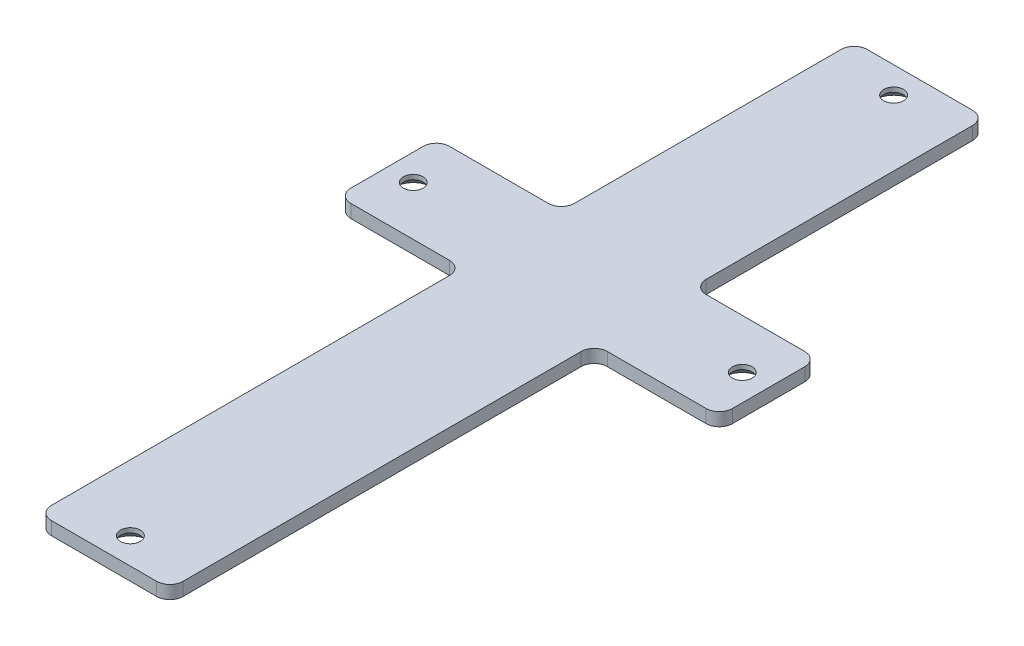
SolidWorks part; units mm, degrees
ref_plane "Front Plane" through (0, 0, 0) normal (0, 0, 1) x (1, 0, 0)
ref_plane "Top Plane" through (0, 0, 0) normal (0, 1, 0) x (1, 0, 0)
ref_plane "Right Plane" through (0, 0, 0) normal (1, 0, 0) x (0, 0, -1)
sketch "Sketch1" plane through (0, 0, 0) normal (0, 1, 0) x (1, 0, 0)
  line L0 (12, 17.5) -> (27, 17.5)
  line L1 (-8, -62) -> (8, -62)
  line L2 (-10, -60) -> (-10, 0.5)
  line L3 (-8, 62) -> (8, 62)
  line L4 (10, -60) -> (10, 0.5)
  line L5 (-10, -62) -> (10, 62) construction
  line L6 (-10, 62) -> (10, -62) construction
  line L7 (-27, 2.5) -> (-12, 2.5)
  line L8 (-29, 4.5) -> (-29, 15.5)
  line L9 (-27, 17.5) -> (-12, 17.5)
  line L10 (29, 4.5) -> (29, 15.5)
  line L11 (-29, 2.5) -> (29, 17.5) construction
  line L12 (-29, 17.5) -> (29, 2.5) construction
  line L13 (10, 19.5) -> (10, 60)
  line L14 (-10, 19.5) -> (-10, 60)
  line L16 (12, 2.5) -> (27, 2.5)
  circle A0 centre (0, 58) radius 1.5
  circle A1 centre (0, -58) radius 1.5
  circle A2 centre (25, 10) radius 1.5
  circle A3 centre (-25, 10) radius 1.5
  arc A4 (-10, 60) -> (-8, 62) centre (-8, 60) cw
  arc A5 (10, 0.5) -> (12, 2.5) centre (12, 0.5) cw
  arc A6 (-12, 17.5) -> (-10, 19.5) centre (-12, 19.5) ccw
  arc A7 (-27, 2.5) -> (-29, 4.5) centre (-27, 4.5) cw
  arc A8 (27, 17.5) -> (29, 15.5) centre (27, 15.5) cw
  arc A9 (-8, -62) -> (-10, -60) centre (-8, -60) cw
  arc A10 (8, 62) -> (10, 60) centre (8, 60) cw
  arc A11 (8, -62) -> (10, -60) centre (8, -60) ccw
  arc A12 (27, 2.5) -> (29, 4.5) centre (27, 4.5) ccw
  arc A13 (-29, 15.5) -> (-27, 17.5) centre (-27, 15.5) cw
  arc A14 (12, 17.5) -> (10, 19.5) centre (12, 19.5) cw
  arc A15 (-10, 0.5) -> (-12, 2.5) centre (-12, 0.5) ccw
  point P0 (0, 0)
  point P6 (0, 10)
  point P30 (10, 2.5)
  point P33 (-10, 17.5)
  point P58 (10, 17.5)
  dimension "D7" = 4
  dimension "D6" = 3
  dimension "D11" = 2
  dimension "D12" = 2
  dimension "D1" = 124
  dimension "D2" = 58
  dimension "D3" = 20
  dimension "D4" = 15
  dimension "D5" = 10
  dimension "D8" = 116
  dimension "D9" = 4
  dimension "D10" = 50
extrude "Boss-Extrude1" add sketch "Sketch1" along normal blind 2
hole_wizard "CSK for M3 SFHCS1" positions "3DSketch1" profile "Sketch2" countersink size "M3" standard "ANSI Metric"
sketch3d "3DSketch1"
  line L5 (25, 2, -10) -> (25, 0, -10) construction
  line L7 (-25, 2, -10) -> (-25, 0, -10) construction
  line L8 (0, 2, 58) -> (0, 0, 58) construction
  line L9 (0, 2, -58) -> (0, 0, -58) construction
  point P20 (25, 0, -10)
  point P28 (-25, 0, -10)
  point P32 (0, 0, 58)
  point P39 (0, 0, -58)
sketch "Sketch2" plane through (25, 0, -10) normal (1, 0, 0) x (0, 0, -1)
  line L0 (0, 0) -> (0, 10.4013)
  line L1 (0, 10.4013) -> (1.5, 9.5)
  line L2 (1.5, 9.5) -> (1.5, 1.3)
  line L3 (1.5, 1.3) -> (2.8, 0)
  line L5 (2.8, 0) -> (0, 0)
  line L6 (-1.5, 1.3) -> (-2.8, 0) construction
  line L10 (0, 10.4013) -> (-1.5, 9.5) construction
  line L11 (0, -6.35) -> (0, 107.95) construction
  dimension "Hole Dia." = 3
  dimension "Hole Depth" = 9.5
  dimension "Near C'Sink Dia." = 5.6
  dimension "Near C'Sink Angle" = 90
  dimension "Drill Angle" = 118
